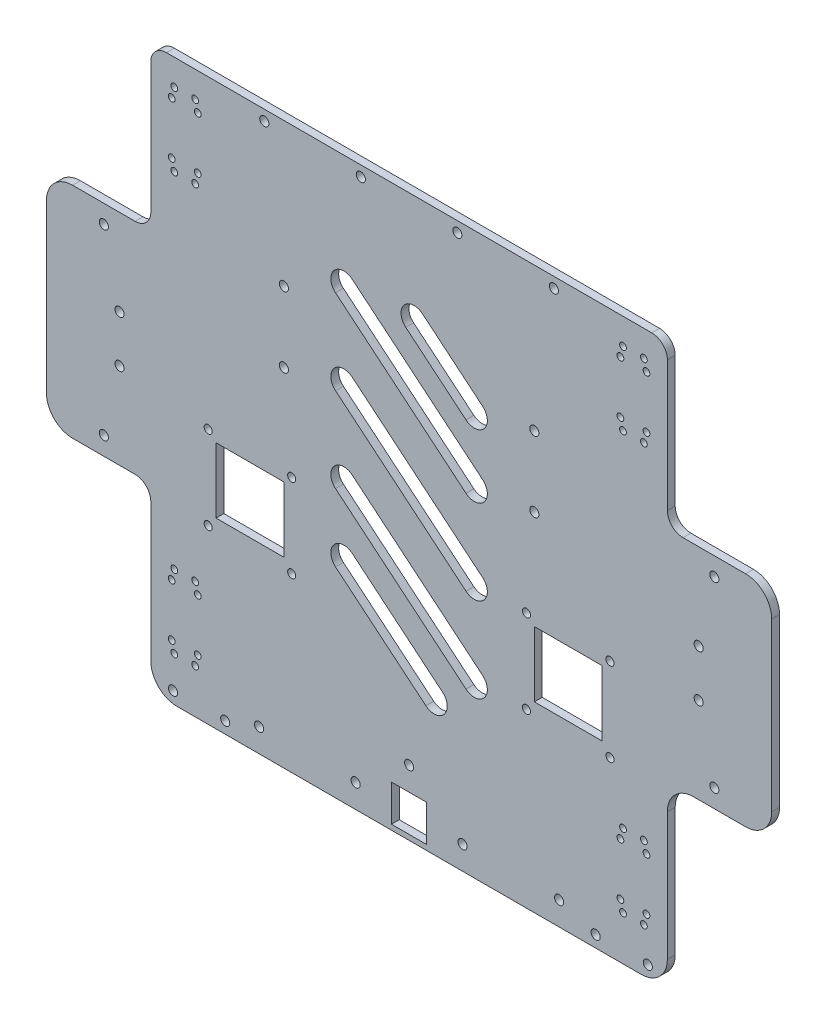
SolidWorks part; units mm, degrees
ref_plane "前视基准面" through (0, 0, 0) normal (0, 0, 1) x (1, 0, 0)
ref_plane "上视基准面" through (0, 0, 0) normal (0, 1, 0) x (1, 0, 0)
ref_plane "右视基准面" through (0, 0, 0) normal (1, 0, 0) x (0, 0, -1)
other "Configuration Table"
sketch "草图1" plane through (0, 0, 0) normal (0, 0, 1) x (1, 0, 0)
  line L1 (-139, 105) -> (139, 105)
  line L2 (-139, 105) -> (-139, -105)
  line L3 (-139, -105) -> (139, -105)
  line L4 (139, 105) -> (139, -105)
  line L5 (0, -105) -> (0, 105) construction
  line L6 (-139, 0) -> (139, 0) construction
  point P0 (0, 0)
  dimension "D1" = 278
  dimension "D2" = 210
extrude "凸台-拉伸1" add sketch "草图1" along normal blind 3
sketch "草图2" plane through (0, 0, 3) normal (0, 0, 1) x (1, 0, 0)
  line L1 (-139, 105) -> (-99, 105)
  line L2 (-139, 105) -> (-139, 43)
  line L3 (-139, 43) -> (-99, 43)
  line L4 (-99, 105) -> (-99, 43)
  line L5 (139, 105) -> (99, 105)
  line L6 (139, 105) -> (139, 43)
  line L7 (139, 43) -> (99, 43)
  line L8 (99, 105) -> (99, 43)
  line L9 (-139, -105) -> (-99, -105)
  line L10 (-139, -105) -> (-139, -41)
  line L11 (-139, -41) -> (-99, -41)
  line L12 (-99, -105) -> (-99, -41)
  line L13 (139, -105) -> (99, -105)
  line L14 (139, -105) -> (139, -41)
  line L15 (139, -41) -> (99, -41)
  line L16 (99, -105) -> (99, -41)
extrude "切除-拉伸1" cut sketch "草图2" against normal blind 3
sketch "草图3" plane through (0, 0, 3) normal (0, 0, 1) x (1, 0, 0)
  line L0 (-99, 43) -> (-99, 105) construction
  line L1 (99, 43) -> (139, 43) construction
  line L2 (-139, 43) -> (-99, 43) construction
  line L5 (99, 105) -> (99, 43) construction
  circle A0 centre (-90, 95) radius 1.2
  circle A1 centre (-90, 67) radius 1.2
  circle A2 centre (-82, 95) radius 1.2
  circle A3 centre (-82, 67) radius 1.2
  circle A4 centre (82, 95) radius 1.2
  circle A5 centre (90, 95) radius 1.2
  circle A6 centre (90, 67) radius 1.2
  circle A7 centre (82, 67) radius 1.2
  dimension "D5" = 2.4
  dimension "D6" = 2.4
  dimension "D8" = 2.4
  dimension "D11" = 2.4
  dimension "D13" = 2.4
  dimension "D14" = 2.4
  dimension "D15" = 2.4
  dimension "D17" = 2.4
  dimension "D1" = 9
  dimension "D2" = 28
  dimension "D3" = 9
  dimension "D4" = 24
  dimension "D7" = 8
  dimension "D9" = 8
  dimension "D10" = 24
  dimension "D12" = 28
  dimension "D16" = 9
  dimension "D18" = 8
  dimension "D19" = 9
  dimension "D20" = 24
  dimension "D21" = 28
  dimension "D22" = 24
  dimension "D23" = 8
extrude "切除-拉伸2" cut sketch "草图3" against normal blind 3
sketch "草图4" plane through (0, 0, 3) normal (0, 0, 1) x (1, 0, 0)
  line L0 (99, 105) -> (-99, 105) construction
  line L1 (-78, 105) -> (78, 105)
  line L2 (-78, 105) -> (-78, 101)
  line L3 (-78, 101) -> (78, 101)
  line L4 (78, 105) -> (78, 101)
  line L5 (-99, 43) -> (-99, 105) construction
  line L6 (99, 105) -> (99, 43) construction
  dimension "D1" = 4
  dimension "D2" = 21
  dimension "D3" = 21
sketch "草图5" plane through (0, 0, 3) normal (0, 0, 1) x (1, 0, 0)
  line L0 (-99, -41) -> (-139, -41) construction
  line L1 (-99, -105) -> (-99, -41) construction
  line L2 (139, -41) -> (99, -41) construction
  line L3 (99, -41) -> (99, -105) construction
  circle A0 centre (-90, -65) radius 1.3
  circle A1 centre (-90, -93) radius 1.3
  circle A2 centre (-82, -65) radius 1.3
  circle A3 centre (-82, -93) radius 1.3
  circle A4 centre (90, -65) radius 1.3
  circle A5 centre (82, -65) radius 1.3
  circle A6 centre (82, -93) radius 1.3
  circle A7 centre (90, -93) radius 1.3
  dimension "D4" = 2.6
  dimension "D5" = 2.6
  dimension "D10" = 2.6
  dimension "D11" = 2.6
  dimension "D18" = 2.6
  dimension "D19" = 2.6
  dimension "D20" = 2.6
  dimension "D21" = 2.6
  dimension "D1" = 24
  dimension "D2" = 28
  dimension "D3" = 9
  dimension "D6" = 24
  dimension "D7" = 8
  dimension "D8" = 28
  dimension "D9" = 8
  dimension "D12" = 24
  dimension "D13" = 9
  dimension "D14" = 24
  dimension "D15" = 9
  dimension "D16" = 8
  dimension "D17" = 28
  dimension "D22" = 8
extrude "切除-拉伸4" cut sketch "草图5" against normal blind 3
sketch "草图7" plane through (0, 0, 3) normal (0, 0, 1) x (1, 0, 0)
  line L2 (-99, -105) -> (-99, -41) construction
  line L3 (-99, -105) -> (99, -105) construction
  circle A0 centre (-57.5, -101) radius 1.75
  circle A1 centre (-20.5, -101) radius 1.75
  circle A2 centre (20.5, -101) radius 1.75
  circle A3 centre (57.5, -101) radius 1.75
  dimension "D1" = 4
  dimension "41.5" = 41.5
  dimension "D2" = 37
  dimension "D3" = 4
  dimension "D4" = 41
  dimension "D5" = 4
  dimension "D6" = 37
  dimension "D7" = 4
extrude "切除-拉伸5" cut sketch "草图7" against normal blind 3
sketch "草图8" plane through (0, 0, 3) normal (0, 0, 1) x (1, 0, 0)
  line L1 (-99, -105) -> (99, -105)
  line L2 (-99, -105) -> (-99, -110)
  line L3 (-99, -110) -> (99, -110)
  line L4 (99, -105) -> (99, -110)
extrude "凸台-拉伸2" add sketch "草图8" against normal blind 3
sketch "草图9" plane through (0, 0, 3) normal (0, 0, 1) x (1, 0, 0)
  line L0 (-99, -110) -> (99, -110) construction
  line L1 (-6.75, -94) -> (6.75, -94)
  line L2 (-6.75, -94) -> (-6.75, -108)
  line L3 (-6.75, -108) -> (6.75, -108)
  line L4 (6.75, -94) -> (6.75, -108)
  circle A0 centre (0, -85) radius 1.75
  point P6 (-20.5, -101)
  point P7 (20.5, -101)
  dimension "D1" = 2
  dimension "D2" = 14
  dimension "D3" = 13.5
  dimension "D4" = 13.75
  dimension "D5" = 9
  dimension "D6" = 6.75
extrude "切除-拉伸6" cut sketch "草图9" against normal blind 3
sketch "草图11" plane through (0, 0, 3) normal (0, 0, 1) x (1, 0, 0)
  line L0 (-78, 101) -> (78, 101) construction
  line L1 (99, 105) -> (99, 43) construction
  line L2 (-78, 105) -> (78, 105) construction
  line L4 (-99, 43) -> (-99, 105) construction
  circle A0 centre (-55.5, 101) radius 1.75
  circle A1 centre (-18.5, 101) radius 1.75
  circle A2 centre (18.5, 101) radius 1.75
  circle A3 centre (55.5, 101) radius 1.75
  dimension "D6" = 3.5
  dimension "D7" = 3.5
  dimension "D8" = 3.5
  dimension "D9" = 3.5
  dimension "D1" = 37
  dimension "D2" = 4
  dimension "D3" = 4
  dimension "D4" = 43.5
  dimension "D5" = 37
  dimension "D10" = 37
  dimension "D11" = 43.5
extrude "切除-拉伸7" cut sketch "草图11" against normal blind 3
sketch "草图12" plane through (0, 0, 3) normal (0, 0, 1) x (1, 0, 0)
  line L0 (-139, 43) -> (-139, -41) construction
  line L1 (-74, -15) -> (-48, -15)
  line L2 (-74, -15) -> (-74, -40)
  line L3 (-74, -40) -> (-48, -40)
  line L4 (-48, -15) -> (-48, -40)
  line L5 (-61, -40) -> (-61, -15) construction
  line L6 (-74, -27.5) -> (-48, -27.5) construction
  line L7 (48, -15) -> (74, -15)
  line L8 (48, -15) -> (48, -40)
  line L9 (48, -40) -> (74, -40)
  line L10 (74, -15) -> (74, -40)
  line L11 (61, -40) -> (61, -15) construction
  line L12 (48, -27.5) -> (74, -27.5) construction
  line L13 (-99, -110) -> (-99, -41) construction
  line L14 (-99, -110) -> (99, -110) construction
  line L15 (99, -41) -> (99, -110) construction
  line L16 (139, -41) -> (139, 43) construction
  circle A0 centre (-77, -12) radius 1.55
  circle A1 centre (-45, -12) radius 1.55
  circle A2 centre (-77, -44) radius 1.55
  circle A3 centre (-45, -44) radius 1.55
  circle A4 centre (45, -12) radius 1.55
  circle A5 centre (77, -12) radius 1.55
  circle A6 centre (45, -44) radius 1.55
  circle A7 centre (77, -44) radius 1.55
  point P8 (-61, -27.5)
  point P20 (61, -27.5)
  dimension "D1" = 3.1
  dimension "D4" = 3.1
  dimension "D9" = 3.1
  dimension "D10" = 3.1
  dimension "D5" = 3.1
  dimension "D8" = 3.1
  dimension "D11" = 3.1
  dimension "D12" = 3.1
  dimension "D2" = 32
  dimension "D3" = 32
  dimension "D6" = 32
  dimension "D7" = 32
  dimension "D13" = 25
  dimension "D14" = 38
  dimension "D15" = 38
  dimension "D16" = 26
  dimension "D17" = 25
  dimension "D18" = 70
  dimension "D19" = 26
  dimension "D20" = 70
  dimension "D21" = 62
  dimension "D22" = 32
  dimension "D23" = 62
  dimension "D24" = 32
extrude "切除-拉伸8" cut sketch "草图12" against normal blind 3
fillet "圆角1" radius 6 1 edges at (-99, 105, 1.5)
fillet "圆角2" radius 6 1 edges at (99, 105, 1.5)
fillet "圆角3" radius 6 1 edges at (-99, 43, 1.5)
fillet "圆角4" radius 10 1 edges at (-139, 43, 1.5)
fillet "圆角5" radius 10 1 edges at (-139, -41, 1.5)
fillet "圆角6" radius 6 1 edges at (-99, -41, 1.5)
fillet "圆角7" radius 6 1 edges at (99, 43, 1.5)
fillet "圆角8" radius 10 1 edges at (139, 43, 1.5)
fillet "圆角9" radius 10 1 edges at (139, -41, 1.5)
fillet "圆角10" radius 10 1 edges at (-99, -110, 1.5)
fillet "圆角11" radius 10 1 edges at (99, -110, 1.5)
sketch "草图17" plane through (0, 0, 3) normal (0, 0, 1) x (1, 0, 0)
  circle A0 centre (-117, 36) radius 1.75
  circle A1 centre (-111, 10) radius 1.75
  circle A2 centre (-111, -8) radius 1.75
  circle A3 centre (-117, -34) radius 1.75
extrude "切除-拉伸9" cut sketch "草图17" against normal blind 3
sketch "草图18" plane through (0, 0, 3) normal (0, 0, 1) x (1, 0, 0)
  circle A0 centre (111, 10) radius 1.75
  circle A1 centre (117, 36) radius 1.75
  circle A2 centre (111, -8) radius 1.75
  circle A3 centre (117, -34) radius 1.75
extrude "切除-拉伸10" cut sketch "草图18" against normal blind 3
sketch "草图22" plane through (0, 0, 3) normal (0, 0, 1) x (1, 0, 0)
  circle A0 centre (-90.4841, -105.5055) radius 1.75
  circle A2 centre (-70.4841, -105.5055) radius 1.75
  circle A3 centre (71.5159, -105.5055) radius 1.75
  circle A5 centre (91.5159, -105.5055) radius 1.75
extrude "切除-拉伸11" cut sketch "草图22" against normal blind 3
fillet "圆角12" radius 10 1 edges at (99, -41, 1.5)
sketch "草图23" plane through (0, 0, 3) normal (0, 0, 1) x (1, 0, 0)
  line L0 (93, 105) -> (-93, 105) construction
  line L1 (-99, -100) -> (-99, -47) construction
  line L2 (-99, 49) -> (-99, 99) construction
  line L3 (99, 99) -> (99, 49) construction
  line L4 (-89, -110) -> (89, -110) construction
  line L5 (99, -51) -> (99, -100) construction
  circle A0 centre (-91, 91) radius 1.3
  circle A1 centre (-91, 71) radius 1.3
  circle A2 centre (-81, 91) radius 1.3
  circle A3 centre (-81, 71) radius 1.3
  circle A4 centre (91, 91) radius 1.3
  circle A5 centre (81, 91) radius 1.3
  circle A6 centre (81, 71) radius 1.3
  circle A7 centre (91, 71) radius 1.3
  circle A8 centre (-91, -69) radius 1.3
  circle A9 centre (-91, -89) radius 1.3
  circle A10 centre (-81, -69) radius 1.3
  circle A11 centre (-81, -89) radius 1.3
  circle A12 centre (81, -69) radius 1.3
  circle A13 centre (91, -69) radius 1.3
  circle A14 centre (81, -89) radius 1.3
  circle A15 centre (91, -89) radius 1.3
  dimension "D2" = 2.6
  dimension "D3" = 8
  dimension "D4" = 2.6
  dimension "D7" = 2.6
  dimension "D8" = 2.6
  dimension "D15" = 2.6
  dimension "D16" = 2.6
  dimension "D17" = 2.6
  dimension "D18" = 2.6
  dimension "D24" = 2.6
  dimension "D25" = 2.6
  dimension "D26" = 2.6
  dimension "D27" = 2.6
  dimension "D34" = 2.6
  dimension "D36" = 2.6
  dimension "D37" = 2.6
  dimension "D38" = 2.6
  dimension "D1" = 14
  dimension "D5" = 8
  dimension "D6" = 20
  dimension "D9" = 10
  dimension "D10" = 10
  dimension "D11" = 8
  dimension "D12" = 10
  dimension "D13" = 8
  dimension "D14" = 18
  dimension "D19" = 20
  dimension "D20" = 20
  dimension "D21" = 14
  dimension "D22" = 14
  dimension "D23" = 8
  dimension "D28" = 20
  dimension "D29" = 21
  dimension "D30" = 21
  dimension "D31" = 20
  dimension "D32" = 8
  dimension "D33" = 20
  dimension "D35" = 20
  dimension "D39" = 21
  dimension "D40" = 21
  dimension "D41" = 8
  dimension "D42" = 8
  dimension "D43" = 10
  dimension "D44" = 10
  dimension "D45" = 10
extrude "切除-拉伸12" cut sketch "草图23" against normal blind 10
sketch "草图24" plane through (0, 0, 3) normal (0, 0, 1) x (1, 0, 0)
  circle A0 centre (-90, 95) radius 1.3
  circle A1 centre (-82, 95) radius 1.3
  circle A2 centre (-90, 67) radius 1.3
  circle A3 centre (-82, 67) radius 1.3
  circle A4 centre (82, 95) radius 1.3
  circle A5 centre (90, 95) radius 1.3
  circle A6 centre (82, 67) radius 1.3
  circle A7 centre (90, 67) radius 1.3
  dimension "D1" = 2.6
  dimension "D2" = 2.6
  dimension "D3" = 2.6
  dimension "D4" = 2.6
  dimension "D5" = 2.6
  dimension "D6" = 2.6
  dimension "D7" = 2.6
  dimension "D8" = 2.6
extrude "切除-拉伸13" cut sketch "草图24" against normal blind 10
sketch "草图25" plane through (0, 0, 3) normal (0, 0, 1) x (1, 0, 0)
  circle A0 centre (-48, 50) radius 1.75
  circle A1 centre (-48, 23) radius 1.75
  circle A2 centre (48, 50) radius 1.75
  circle A3 centre (48, 23) radius 1.75
extrude "切除-拉伸14" cut sketch "草图25" against normal blind 3
sketch "草图26" plane through (0, 0, 0) normal (0, 0, -1) x (-1, 0, 0)
  line L0 (25, 61.5331) -> (-25, 20) construction
  line L1 (-35, 70) -> (35, 70)
  line L2 (-35, 70) -> (-35, -70)
  line L3 (-35, -70) -> (35, -70)
  line L4 (35, 70) -> (35, -70)
  line L5 (0, -70) -> (0, 70) construction
  line L6 (-35, 0) -> (35, 0) construction
  line L7 (28.1949, 57.687) -> (-21.8051, 16.1538)
  line L8 (21.8051, 65.3793) -> (-28.1949, 23.8462)
  line L9 (25, 29.0331) -> (-25, -12.5) construction
  line L10 (28.1949, 25.187) -> (-21.8051, -16.3462)
  line L11 (21.8051, 32.8793) -> (-28.1949, -8.6538)
  line L12 (25, -3.4669) -> (-25, -45) construction
  line L13 (28.1949, -7.313) -> (-21.8051, -48.8462)
  line L14 (21.8051, 0.3793) -> (-28.1949, -41.1538)
  line L15 (25, -29.4669) -> (-9.6154, -58.2206) construction
  line L16 (28.1949, -33.313) -> (-6.4205, -62.0667)
  line L17 (21.8051, -25.6207) -> (-12.8102, -54.3744)
  line L18 (-1.9231, 63.5257) -> (-25, 44.3565) construction
  line L19 (1.2718, 59.6795) -> (-21.8051, 40.5104)
  line L20 (-5.1179, 67.3718) -> (-28.1949, 48.2027)
  arc A0 (28.1949, 57.687) -> (21.8051, 65.3793) centre (25, 61.5331) ccw
  arc A1 (-28.1949, 23.8462) -> (-21.8051, 16.1538) centre (-25, 20) ccw
  arc A2 (28.1949, 25.187) -> (21.8051, 32.8793) centre (25, 29.0331) ccw
  arc A3 (-28.1949, -8.6538) -> (-21.8051, -16.3462) centre (-25, -12.5) ccw
  arc A4 (28.1949, -7.313) -> (21.8051, 0.3793) centre (25, -3.4669) ccw
  arc A5 (-28.1949, -41.1538) -> (-21.8051, -48.8462) centre (-25, -45) ccw
  arc A6 (28.1949, -33.313) -> (21.8051, -25.6207) centre (25, -29.4669) ccw
  arc A7 (-12.8102, -54.3744) -> (-6.4205, -62.0667) centre (-9.6154, -58.2206) ccw
  arc A8 (1.2718, 59.6795) -> (-5.1179, 67.3718) centre (-1.9231, 63.5257) ccw
  arc A9 (-28.1949, 48.2027) -> (-21.8051, 40.5104) centre (-25, 44.3565) ccw
  point P0 (0, 0)
  point P6 (0, 40.7666)
  point P11 (0, 8.2666)
  point P18 (0, -24.2334)
  point P25 (7.6923, -43.8437)
  point P32 (-13.4615, 53.9411)
  dimension "D1" = 70
  dimension "D2" = 140
  dimension "D3" = 65
  dimension "D4" = 25
  dimension "D5" = 25
  dimension "D6" = 10
  dimension "D7" = 10
  dimension "D8" = 10
  dimension "D9" = 10
  dimension "D10" = 10
  dimension "D11" = 50
  dimension "D12" = 10
  dimension "D13" = 20
  dimension "D14" = 45
  dimension "D15" = 30
  dimension "D16" = 10
extrude "切除-拉伸15" cut sketch "草图26" against normal through all contours L20 A9 L19 A8 | L8 A1 L7 A0 | L11 A3 L10 A2 | L14 A5 L13 A4 | L17 A7 L16 A6
